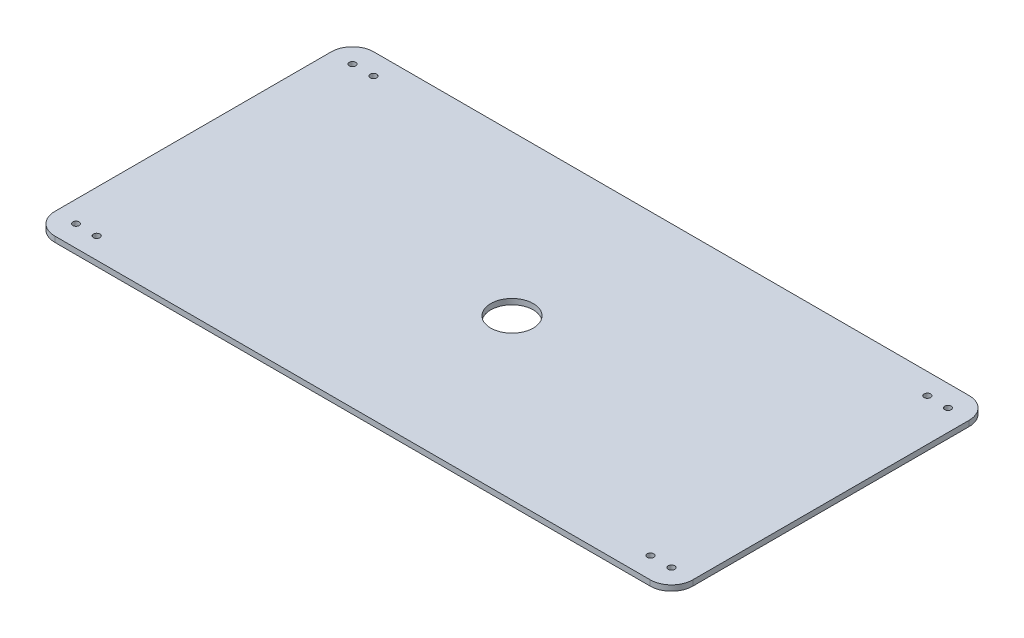
SolidWorks part; units mm, degrees
ref_plane "Front Plane" through (0, 0, 0) normal (0, 0, 1) x (1, 0, 0)
ref_plane "Top Plane" through (0, 0, 0) normal (0, 1, 0) x (1, 0, 0)
ref_plane "Right Plane" through (0, 0, 0) normal (1, 0, 0) x (0, 0, -1)
sketch "Sketch1" plane through (0, 0, 0) normal (0, 1, 0) x (1, 0, 0)
  line L1 (0, 0) -> (300, 0)
  line L2 (0, 0) -> (0, -150)
  line L3 (0, -150) -> (300, -150)
  line L4 (300, 0) -> (300, -150)
  dimension "D1" = 150
  dimension "D2" = 300
extrude "Boss-Extrude1" add sketch "Sketch1" along normal blind 2.6 contours L1 L4 L3 L2
fillet "Fillet1" radius 10 4 edges at (0, 1.3, 0) (0, 1.3, 150) (300, 1.3, 150) (300, 1.3, 0)
sketch "Sketch6" plane through (0, 0, 0) normal (0, -1, 0) x (1, 0, 0)
  line L0 (300, 10) -> (300, 140) construction
  line L1 (10, 0) -> (290, 0) construction
  circle A0 centre (290, 10) radius 1.5
  dimension "D1" = 3
  dimension "D2" = 10
  dimension "D3" = 10
ref_plane "Plane1" through (150, 0, 0) normal (1, 0, 0) x (0, 0, -1)
extrude "Cut-Extrude6" cut sketch "Sketch6" against normal blind 2.6 contours A0
ref_plane "Plane14" through (0, 0, 75) normal (0, 0, 1) x (1, 0, 0)
mirror "Mirror5" about plane through (150, 0, 0) normal (1, 0, 0) of "Cut-Extrude6"
mirror "Mirror6" about plane through (0, 0, 75) normal (0, 0, 1) of "Mirror5", "Cut-Extrude6"
sketch "Sketch15" plane through (0, 0, 0) normal (0, -1, 0) x (1, 0, 0)
  line L0 (150, 0) -> (150, 150) construction
  line L2 (0, 75) -> (300, 75) construction
  line L4 (0, 10) -> (0, 140) construction
  line L5 (300, 10) -> (300, 140) construction
  line L6 (10, 0) -> (290, 0) construction
  line L7 (10, 150) -> (290, 150) construction
  circle A0 centre (150, 75) radius 10
  dimension "D1" = 20
extrude "Cut-Extrude14" cut sketch "Sketch15" against normal through all contours A0
sketch "Sketch23" plane through (0, 2.6, 0) normal (0, 1, 0) x (1, 0, 0)
  circle A0 centre (19.812, -9.906) radius 1.524
extrude "Cut-Extrude16" cut sketch "Sketch23" against normal blind 2.6
mirror "Mirror7" about plane through (150, 0, 0) normal (1, 0, 0) of "Cut-Extrude16"
mirror "Mirror8" about plane through (0, 0, 75) normal (0, 0, 1) of "Mirror7", "Cut-Extrude16"
